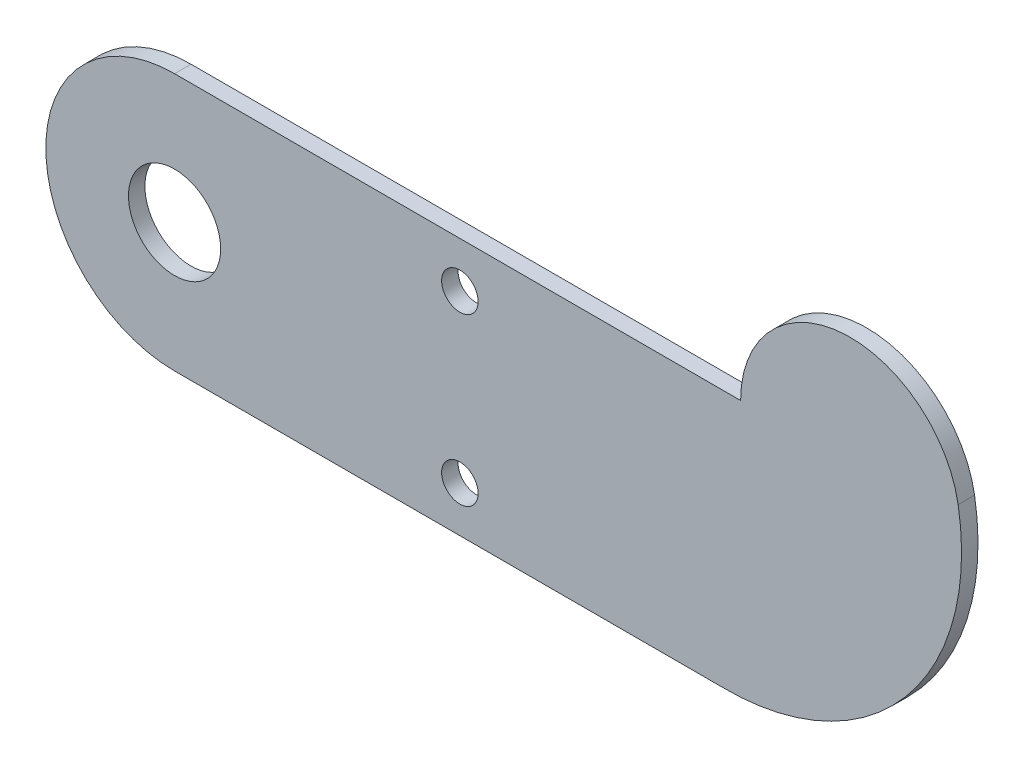
SolidWorks part; units mm, degrees
ref_plane "Plano frontal" through (0, 0, 0) normal (0, 0, 1) x (1, 0, 0)
ref_plane "Plano superior" through (0, 0, 0) normal (0, 1, 0) x (1, 0, 0)
ref_plane "Plano direito" through (0, 0, 0) normal (1, 0, 0) x (0, 0, -1)
sketch "Esboço1" plane through (0, 0, 0) normal (0, 0, 1) x (1, 0, 0)
  line L0 (-12, 0) -> (-74, 0)
  line L1 (-14, -28.2) -> (-74, -28.2)
  arc A0 (-12, 0) -> (11.8263, 2.0344) centre (0, 0) cw
  arc A1 (11.8263, 2.0344) -> (-14, -28.2) centre (-13.6532, -2.3486) cw
  arc A2 (-74, 0) -> (-74, -28.2) centre (-74, -14.1) ccw
  circle A3 centre (-74, -14.1) radius 5.05
  circle A4 centre (-42.75, -5) radius 2
  circle A5 centre (-42.75, -23.2) radius 2
  point P14 (0, 0)
  point P15 (0, 0)
  point P16 (0, 0)
  point P17 (0, 0)
  dimension "D1" = 28.2
  dimension "D2" = 12
  dimension "D3" = 5
  dimension "D4" = 5
  dimension "D5" = 31.25
extrude "Ressalto-extrusão1" add sketch "Esboço1" along normal blind 1.8
sketch "Esboço2" plane through (0, 0, 0) normal (0, 0, 1) x (1, 0, 0)
  circle A0 centre (0, 0) radius 5
extrude "Ressalto-extrusão2" add sketch "Esboço2" against normal blind 1.8
